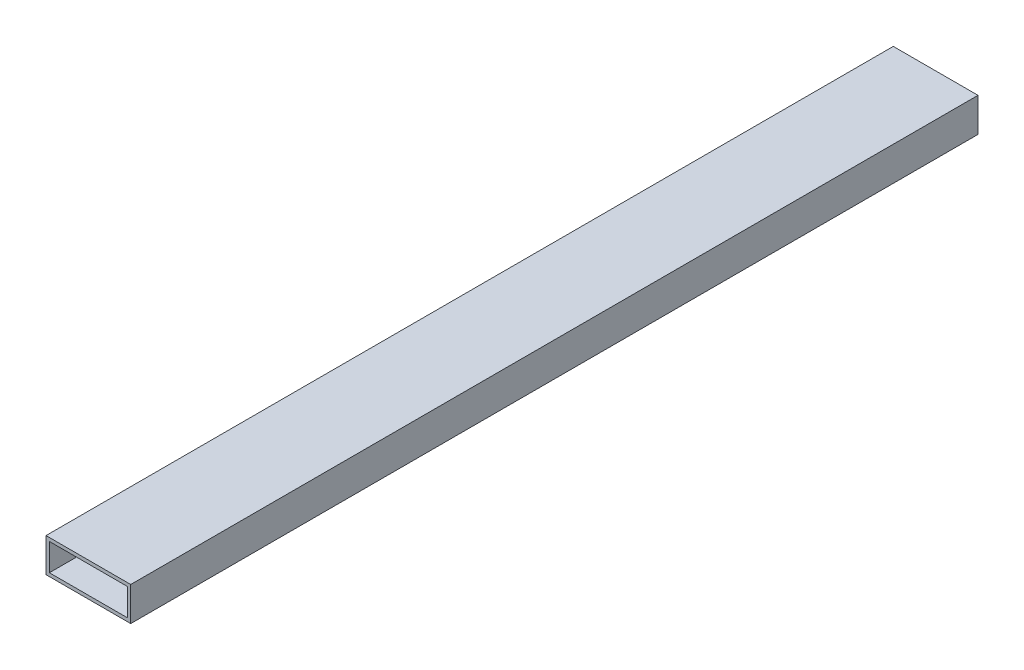
SolidWorks part; units mm, degrees
ref_plane "Спереди" through (0, 0, 0) normal (0, 0, 1) x (1, 0, 0)
ref_plane "Сверху" through (0, 0, 0) normal (0, 1, 0) x (1, 0, 0)
ref_plane "Справа" through (0, 0, 0) normal (1, 0, 0) x (0, 0, -1)
sketch "Эскиз1" plane through (0, 0, 0) normal (0, 0, 1) x (1, 0, 0)
  line L1 (0, 0) -> (50, 0)
  line L2 (0, 0) -> (0, 20)
  line L3 (0, 20) -> (50, 20)
  line L4 (50, 0) -> (50, 20)
  line L5 (2, 2) -> (48, 2)
  line L6 (2, 2) -> (2, 18)
  line L7 (2, 18) -> (48, 18)
  line L8 (48, 2) -> (48, 18)
  point P9 (25, 18)
  point P10 (25, 20)
  point P11 (2, 10)
  point P12 (0, 10)
  dimension "D1" = 2
  dimension "D2" = 20
  dimension "D3" = 50
  dimension "D4" = 2
extrude "Бобышка-Вытянуть1" add sketch "Эскиз1" along normal blind 500
ref_plane "Плоскость1" through (25, 0, 0) normal (1, 0, 0) x (0, 0, -1)
equation "\"D4@Эскиз1\"= \"D1@Эскиз1\""
equation "\"SBR16.Length.X\"= 600мм"
equation "\"SBR16.Length.Y\"= 500мм"
equation "\"SBR16.Length.Z\"= 250мм"
equation "\"D1@Бобышка-Вытянуть1\"= \"SBR16.Length.Y\""
